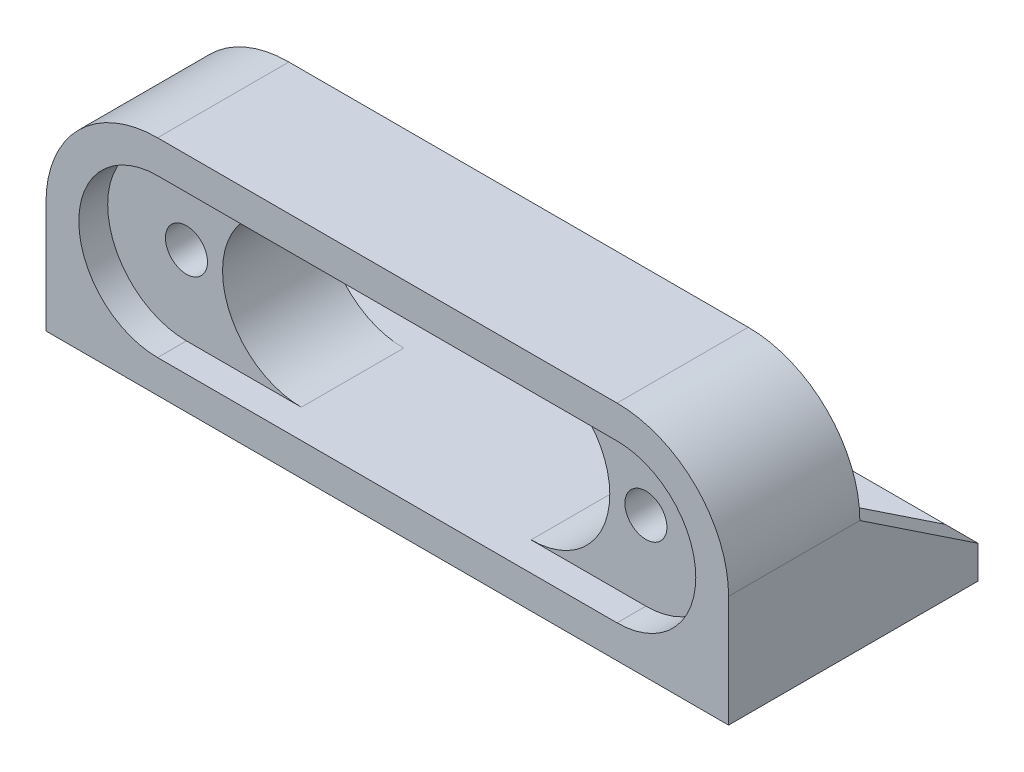
SolidWorks part; units mm, degrees
ref_plane "Plano frontal" through (0, 0, 0) normal (0, 0, 1) x (1, 0, 0)
ref_plane "Plano superior" through (0, 0, 0) normal (0, 1, 0) x (1, 0, 0)
ref_plane "Plano direito" through (0, 0, 0) normal (1, 0, 0) x (0, 0, -1)
sketch "Esboço1" plane through (0, 0, 0) normal (0, 0, 1) x (1, 0, 0)
  line L0 (-26, 0) -> (-26, -8.5)
  line L1 (-17.5, -8.5) -> (-26, -8.5)
  line L2 (17.5, -8.5) -> (26, -8.5)
  line L3 (0, 6) -> (8.75, 6)
  line L4 (0, -6) -> (8.75, -6)
  line L5 (0, 6) -> (-8.75, 6)
  line L6 (0, -6) -> (-8.75, -6)
  line L7 (0, 8.5) -> (17.5, 8.5)
  line L8 (0, 8.5) -> (-17.5, 8.5)
  line L9 (0, -8.5) -> (-17.5, -8.5)
  line L10 (0, -8.5) -> (17.5, -8.5)
  line L11 (26, 0) -> (26, -8.5)
  arc A0 (-8.75, 6) -> (-8.75, -6) centre (-8.75, 0) ccw
  arc A1 (8.75, -6) -> (8.75, 6) centre (8.75, 0) ccw
  circle A2 centre (-17.5, 0) radius 1.6
  circle A3 centre (17.5, 0) radius 1.6
  arc A4 (-17.5, 8.5) -> (-26, 0) centre (-17.5, 0) ccw
  arc A5 (26, 0) -> (17.5, 8.5) centre (17.5, 0) ccw
extrude "Ressalto-extrusão2" add sketch "Esboço1" along normal blind 10
sketch "Esboço2" plane through (0, 0, 10) normal (0, 0, 1) x (1, 0, 0)
  line L0 (0, 6) -> (-17.5, 6)
  line L1 (8.75, 6) -> (-8.75, 6) construction
  line L2 (0, 6) -> (17.5, 6)
  line L3 (0, -6) -> (-17.5, -6)
  line L4 (-8.75, -6) -> (8.75, -6) construction
  line L5 (0, -6) -> (17.5, -6)
  arc A0 (-17.5, 6) -> (-17.5, -6) centre (-17.5, 0) ccw
  arc A1 (17.5, -6) -> (17.5, 6) centre (17.5, 0) ccw
extrude "Corte-extrusão1" cut sketch "Esboço2" against normal blind 2.2
sketch "Esboço3" plane through (0, 0, 0) normal (0, 0, -1) x (-1, 0, 0)
  line L0 (-8.75, -6) -> (-23.5, -6)
  line L1 (-8.75, -6) -> (23.5, -6)
  line L4 (-26, -8.5) -> (26, -8.5)
  line L6 (-26, 0) -> (-23.5, 0)
  line L7 (-23.5, 0) -> (-23.5, -6)
  line L8 (26, 0) -> (26, -8.5)
  line L9 (26, 0) -> (23.5, 0)
  line L10 (23.5, 0) -> (23.5, -6)
  line L12 (-26, 0) -> (-26, -8.5)
extrude "Ressalto-extrusão3" add sketch "Esboço3" along normal blind 9
sketch "Esboço4" plane through (0, -6, 0) normal (0, 1, 0) x (1, 0, 0)
  circle A0 centre (-16.55, 4.5) radius 1.6
  circle A1 centre (16.55, 4.5) radius 1.6
extrude "Corte-extrusão2" cut sketch "Esboço4" against normal blind 9
sketch "Esboço6" plane through (26, 0, 0) normal (1, 0, 0) x (0, 0, -1)
  line L5 (9, -6) -> (0, 0)
  line L6 (0, 0) -> (2.0058, 2.4703)
  line L7 (2.0058, 2.4703) -> (10.4688, 1.9266)
  line L8 (10.4688, 1.9266) -> (11.2489, 0)
  line L9 (11.2489, 0) -> (9, -6)
extrude "Corte-extrusão3" cut sketch "Esboço6" against normal through all
